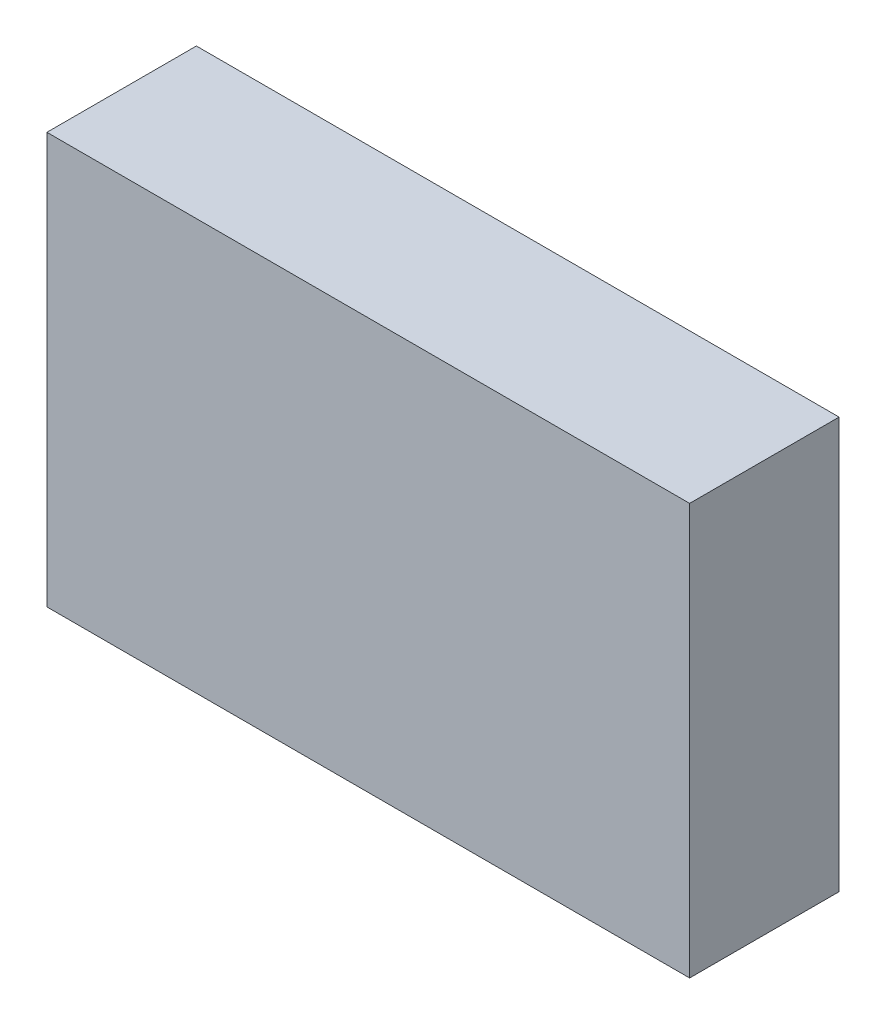
SolidWorks part; units mm, degrees
ref_plane "前视基准面" through (0, 0, 0) normal (0, 0, 1) x (1, 0, 0)
ref_plane "上视基准面" through (0, 0, 0) normal (0, 1, 0) x (1, 0, 0)
ref_plane "右视基准面" through (0, 0, 0) normal (1, 0, 0) x (0, 0, -1)
sketch "草图1" plane through (0, 0, 0) normal (0, 1, 0) x (1, 0, 0)
  line L1 (0, 0) -> (86, 0)
  line L2 (0, 0) -> (0, -20)
  line L3 (0, -20) -> (86, -20)
  line L4 (86, 0) -> (86, -20)
  dimension "D1" = 86
  dimension "D2" = 20
extrude "凸台-拉伸1" add sketch "草图1" along normal blind 55
sketch "草图2" plane through (0, 55, 0) normal (0, 1, 0) x (1, 0, 0)
  line L1 (0, 0) -> (7.6798, 0)
  line L2 (0, 0) -> (0, -15.4651)
  line L3 (0, -15.4651) -> (7.6798, -15.4651)
  line L4 (7.6798, 0) -> (7.6798, -15.4651)
  line L5 (86, 0) -> (80.1268, 0)
  line L6 (86, 0) -> (86, -15.4651)
  line L7 (86, -15.4651) -> (80.1268, -15.4651)
  line L8 (80.1268, 0) -> (80.1268, -15.4651)
